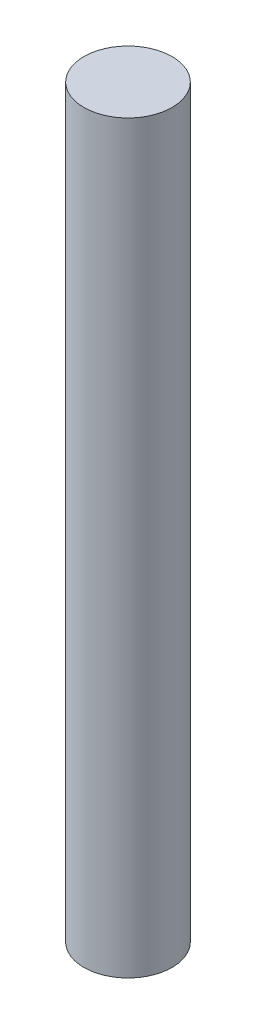
SolidWorks part; units mm, degrees
ref_plane "Front Plane" through (0, 0, 0) normal (0, 0, 1) x (1, 0, 0)
ref_plane "Top Plane" through (0, 0, 0) normal (0, 1, 0) x (1, 0, 0)
ref_plane "Right Plane" through (0, 0, 0) normal (1, 0, 0) x (0, 0, -1)
sketch "Sketch1" plane through (0, 0, 0) normal (0, 1, 0) x (1, 0, 0)
  circle A0 centre (0, 0) radius 14.8
  dimension "D1" = 29.6
extrude "Boss-Extrude1" add sketch "Sketch1" along normal blind 250
